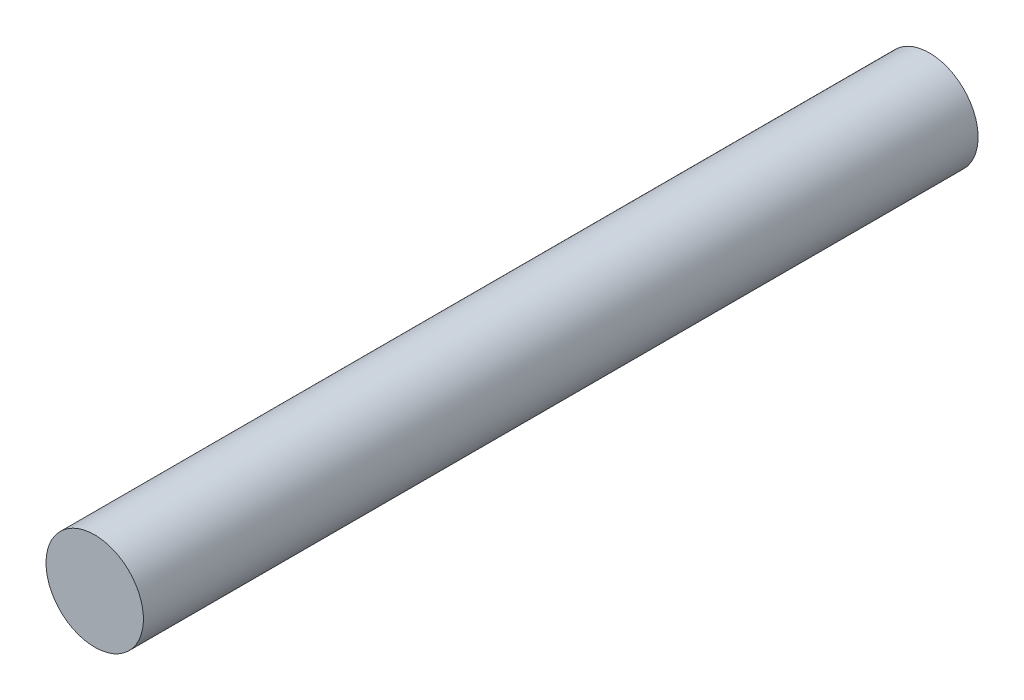
SolidWorks part; units mm, degrees
ref_plane "Front Plane" through (0, 0, 0) normal (0, 0, 1) x (1, 0, 0)
ref_plane "Top Plane" through (0, 0, 0) normal (0, 1, 0) x (1, 0, 0)
ref_plane "Right Plane" through (0, 0, 0) normal (1, 0, 0) x (0, 0, -1)
sketch "Sketch1" plane through (0, 0, 0) normal (0, 0, 1) x (1, 0, 0)
  circle A0 centre (0, 0) radius 2.2225
  dimension "D1" = 4.445
extrude "Boss-Extrude1" add sketch "Sketch1" along normal blind 38.1 contours A0
